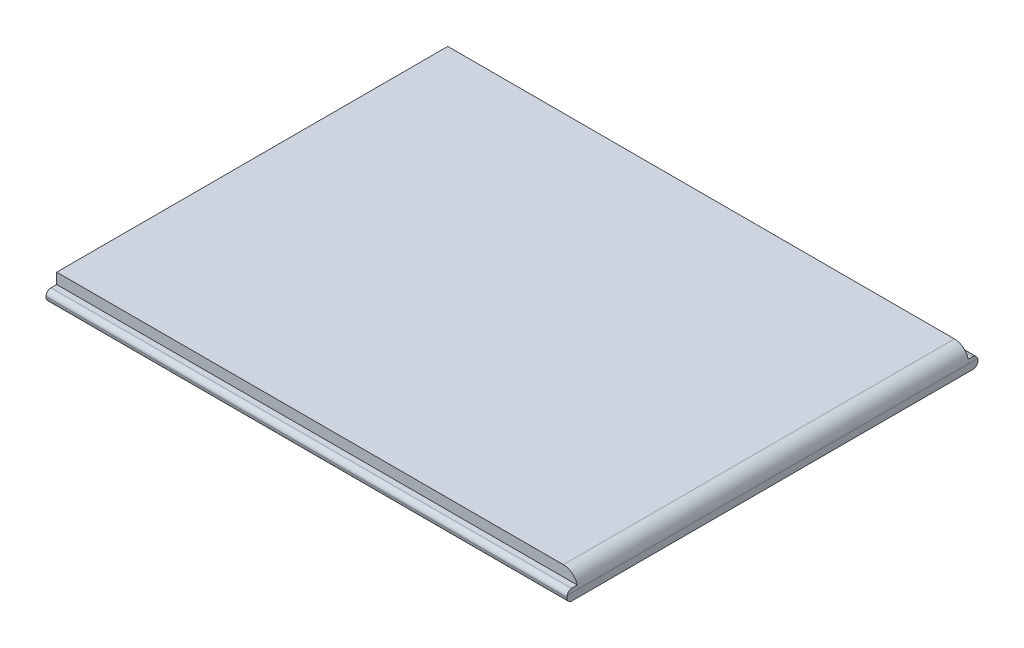
SolidWorks part; units mm, degrees
ref_plane "Alzado" through (0, 0, 0) normal (0, 0, 1) x (1, 0, 0)
ref_plane "Planta" through (0, 0, 0) normal (0, 1, 0) x (1, 0, 0)
ref_plane "Vista lateral" through (0, 0, 0) normal (1, 0, 0) x (0, 0, -1)
sketch "Croquis1" plane through (0, 0, 0) normal (0, 1, 0) x (1, 0, 0)
  line L5 (0, 0) -> (73, 0)
  line L6 (0, 0) -> (0, 57.6)
  line L7 (0, 57.6) -> (73, 57.6)
  line L8 (73, 0) -> (73, 57.6)
  point P4 (0, 0)
  point P5 (0, 0)
  point P7 (0, 0)
  point P8 (0, 0)
extrude "Saliente-Extruir1" add sketch "Croquis1" along normal blind 1.5
sketch "Croquis3" plane through (0, 0, 0) normal (0, 1, 0) x (1, 0, 0)
  line L1 (0, 1.5) -> (73, 1.5)
  line L2 (0, 1.5) -> (0, 56.3)
  line L3 (0, 56.3) -> (73, 56.3)
  line L4 (73, 1.5) -> (73, 56.3)
  point P4 (0, 0)
  point P5 (0, 0)
  point P6 (0, 0)
extrude "Saliente-Extruir2" add sketch "Croquis3" along normal blind 3 contours L2 L1 L4 L3
fillet "Redondeo1" radius 2 1 edges at (73, 3, -28.9)
fillet "Redondeo4" radius 0.7 2 edges at (36.5, 0, 0) (36.4682, 1.5, 0)
fillet "Redondeo5" radius 0.7 2 edges at (36.5, 0, -57.6) (36.4682, 1.5, -57.6)
